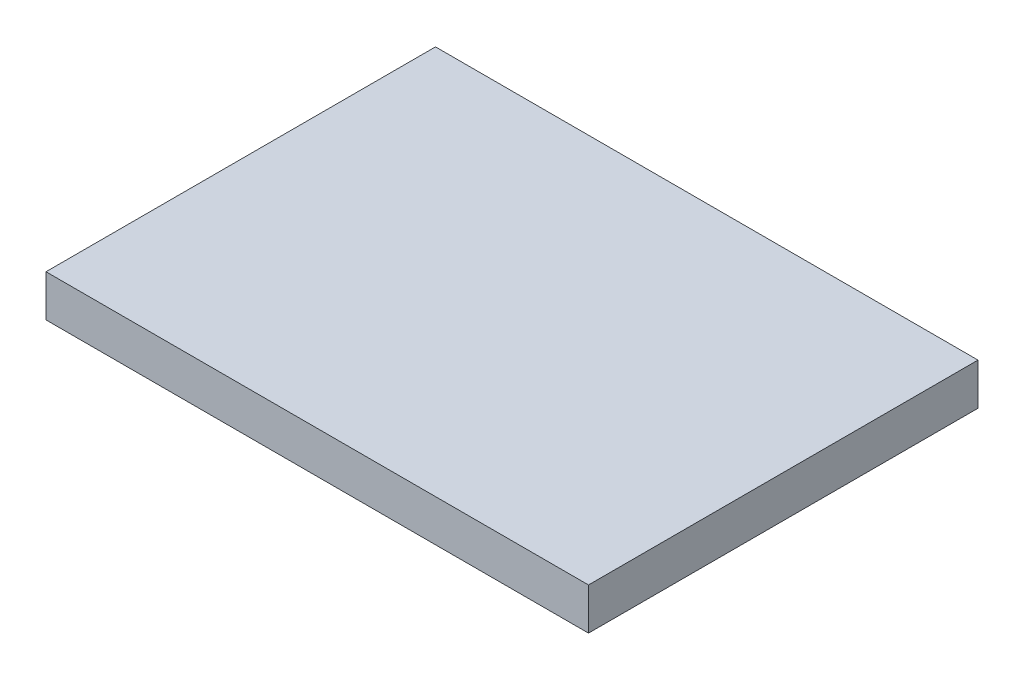
SolidWorks part; units mm, degrees
material "Polyurethane Foam Rigid"
ref_plane "Front Plane" through (0, 0, 0) normal (0, 0, 1) x (1, 0, 0)
ref_plane "Top Plane" through (0, 0, 0) normal (0, 1, 0) x (1, 0, 0)
ref_plane "Right Plane" through (0, 0, 0) normal (1, 0, 0) x (0, 0, -1)
sketch "Sketch1" plane through (0, 0, 0) normal (0, 1, 0) x (1, 0, 0)
  line L1 (-247.65, -177.8) -> (247.65, -177.8)
  line L2 (-247.65, -177.8) -> (-247.65, 177.8)
  line L3 (-247.65, 177.8) -> (247.65, 177.8)
  line L4 (247.65, -177.8) -> (247.65, 177.8)
  line L5 (-247.65, -177.8) -> (247.65, 177.8) construction
  line L6 (-247.65, 177.8) -> (247.65, -177.8) construction
  point P0 (0, 0)
extrude "Boss-Extrude1" add sketch "Sketch1" along normal blind 38.1
